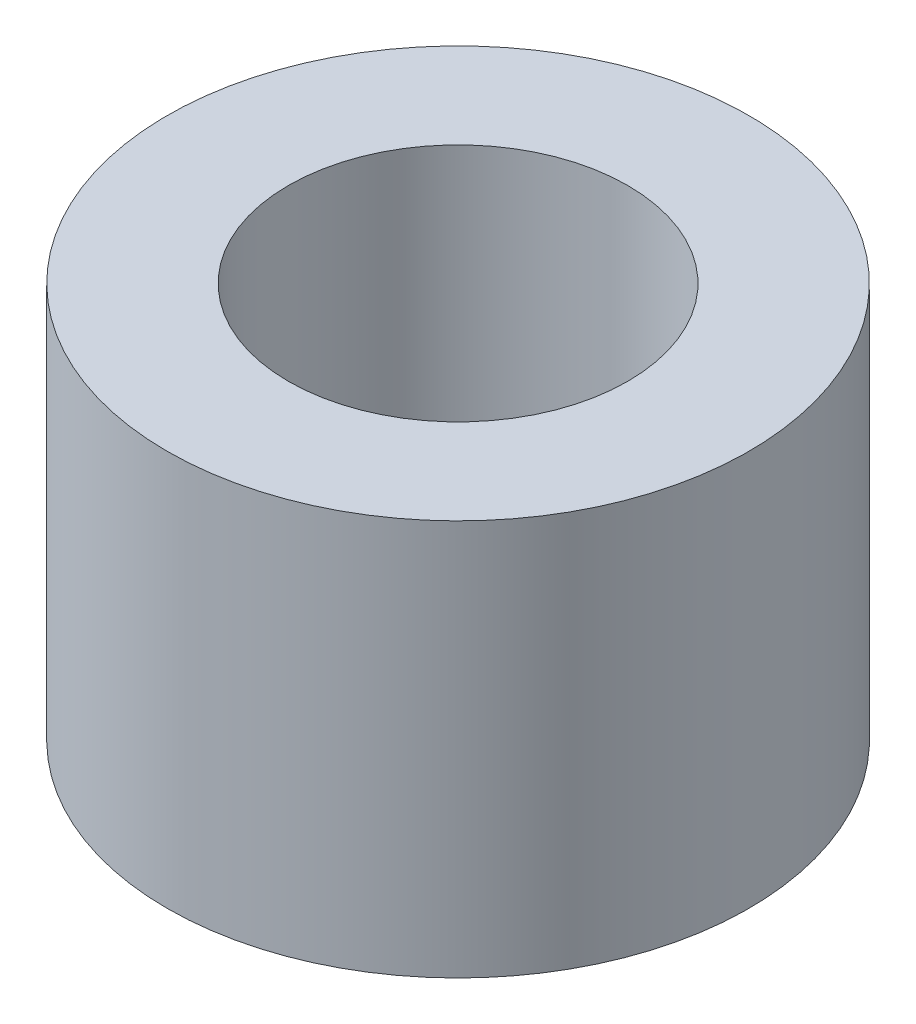
SolidWorks part; units mm, degrees
ref_plane "Front Plane" through (0, 0, 0) normal (0, 0, 1) x (1, 0, 0)
ref_plane "Top Plane" through (0, 0, 0) normal (0, 1, 0) x (1, 0, 0)
ref_plane "Right Plane" through (0, 0, 0) normal (1, 0, 0) x (0, 0, -1)
sketch "Sketch1" plane through (0, 0, 0) normal (0, 1, 0) x (1, 0, 0)
  circle A0 centre (0, 0) radius 2.1
  circle A1 centre (0, 0) radius 3.6
  dimension "D1" = 7.2
  dimension "D2" = 4.2
extrude "Boss-Extrude1" add sketch "Sketch1" along normal blind 4.9
